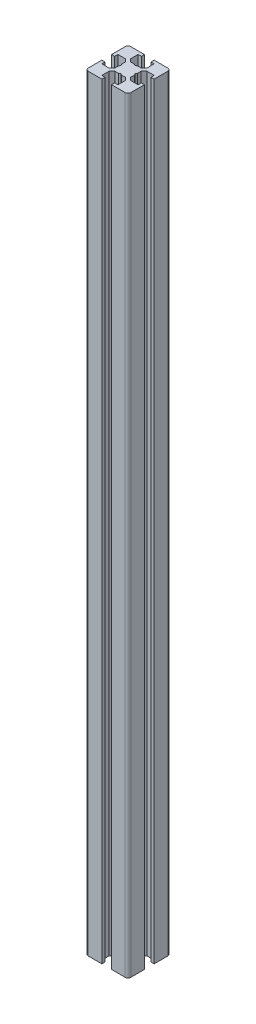
SolidWorks part; units mm, degrees
ref_plane "Front Plane" through (0, 0, 0) normal (0, 0, 1) x (1, 0, 0)
ref_plane "Top Plane" through (0, 0, 0) normal (0, 1, 0) x (1, 0, 0)
ref_plane "Right Plane" through (0, 0, 0) normal (1, 0, 0) x (0, 0, -1)
sketch "Sketch2" plane through (0, 0, 0) normal (0, 1, 0) x (1, 0, 0)
  line L3 (1.7, 7.5) -> (6.5, 7.5)
  line L5 (0, 2.5) -> (-0.5196, 2.8)
  line L6 (-2.85, 3.8) -> (-1.85, 2.8)
  line L9 (1.7, 6.4) -> (1.7, 7.5)
  line L10 (1.7, 6.4) -> (2.85, 6.4)
  line L11 (2.85, 6.4) -> (2.85, 3.8)
  line L12 (2.85, 3.8) -> (1.85, 2.8)
  line L13 (1.85, 2.8) -> (0.5196, 2.8)
  line L14 (2.8, -0.5196) -> (2.8, -1.85)
  line L15 (0, 2.5) -> (0.5196, 2.8)
  line L16 (-2.85, 6.4) -> (-2.85, 3.8)
  line L17 (-1.7, 6.4) -> (-2.85, 6.4)
  line L18 (-1.7, 6.4) -> (-1.7, 7.5)
  line L19 (-1.7, 7.5) -> (-6.5, 7.5)
  line L21 (7.5, -1.7) -> (7.5, -6.5)
  line L22 (6.4, -1.7) -> (7.5, -1.7)
  line L23 (6.4, -1.7) -> (6.4, -2.85)
  line L24 (6.4, -2.85) -> (3.8, -2.85)
  line L25 (2.5, 0) -> (2.8, 0.5196)
  line L26 (0.5196, -2.8) -> (1.85, -2.8)
  line L27 (2.8, 1.85) -> (2.8, 0.5196)
  line L28 (3.8, 2.85) -> (2.8, 1.85)
  line L29 (6.4, 2.85) -> (3.8, 2.85)
  line L30 (6.4, 1.7) -> (6.4, 2.85)
  line L31 (6.4, 1.7) -> (7.5, 1.7)
  line L32 (3.8, -2.85) -> (2.8, -1.85)
  line L33 (2.5, 0) -> (2.8, -0.5196)
  line L34 (7.5, 1.7) -> (7.5, 6.5)
  line L36 (-1.7, -6.4) -> (-1.7, -7.5)
  line L37 (0, -2.5) -> (0.5196, -2.8)
  line L38 (2.85, -3.8) -> (1.85, -2.8)
  line L39 (-1.85, -2.8) -> (-0.5196, -2.8)
  line L41 (0, -2.5) -> (-0.5196, -2.8)
  line L42 (2.85, -6.4) -> (2.85, -3.8)
  line L43 (1.7, -6.4) -> (2.85, -6.4)
  line L44 (1.7, -6.4) -> (1.7, -7.5)
  line L45 (1.7, -7.5) -> (6.5, -7.5)
  line L46 (-1.7, -7.5) -> (-6.5, -7.5)
  line L47 (-1.7, -6.4) -> (-2.85, -6.4)
  line L48 (-2.85, -6.4) -> (-2.85, -3.8)
  line L49 (-2.85, -3.8) -> (-1.85, -2.8)
  line L50 (-7.5, 1.7) -> (-7.5, 6.5)
  line L51 (-6.4, 1.7) -> (-7.5, 1.7)
  line L52 (-6.4, 1.7) -> (-6.4, 2.85)
  line L53 (-6.4, 2.85) -> (-3.8, 2.85)
  line L54 (-2.5, 0) -> (-2.8, -0.5196)
  line L55 (-0.5196, 2.8) -> (-1.85, 2.8)
  line L56 (-2.8, -1.85) -> (-2.8, -0.5196)
  line L57 (-3.8, -2.85) -> (-2.8, -1.85)
  line L58 (-6.4, -2.85) -> (-3.8, -2.85)
  line L59 (-6.4, -1.7) -> (-6.4, -2.85)
  line L60 (-6.4, -1.7) -> (-7.5, -1.7)
  line L61 (-3.8, 2.85) -> (-2.8, 1.85)
  line L62 (-2.5, 0) -> (-2.8, 0.5196)
  line L63 (-7.5, -1.7) -> (-7.5, -6.5)
  line L64 (-2.8, 0.5196) -> (-2.8, 1.85)
  arc A0 (7.5, 6.5) -> (6.5, 7.5) centre (6.5, 6.5) ccw
  arc A1 (-7.5, 6.5) -> (-6.5, 7.5) centre (-6.5, 6.5) cw
  arc A2 (6.5, -7.5) -> (7.5, -6.5) centre (6.5, -6.5) ccw
  arc A3 (-6.5, -7.5) -> (-7.5, -6.5) centre (-6.5, -6.5) cw
  dimension "D11" = 2
  dimension "D2" = 3.4
  dimension "D3" = 5.7
  dimension "D6" = 2.6
  dimension "D7" = 1
  dimension "D8" = 1
extrude "Boss-Extrude1" add sketch "Sketch2" along normal blind 270
